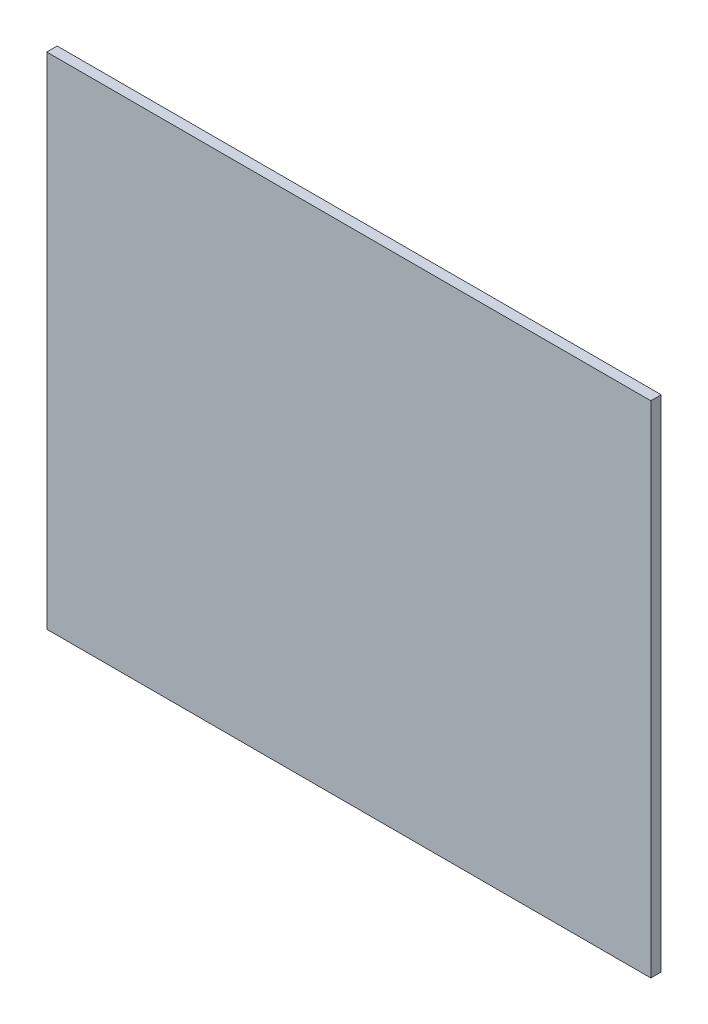
SolidWorks part; units mm, degrees
ref_plane "前视基准面" through (0, 0, 0) normal (0, 0, 1) x (1, 0, 0)
ref_plane "上视基准面" through (0, 0, 0) normal (0, 1, 0) x (1, 0, 0)
ref_plane "右视基准面" through (0, 0, 0) normal (1, 0, 0) x (0, 0, -1)
sketch "草图1" plane through (0, 0, 0) normal (0, 0, 1) x (1, 0, 0)
  line L1 (-29, 24) -> (0, 24)
  line L2 (-29, 24) -> (-29, 0)
  line L3 (-29, 0) -> (0, 0)
  line L4 (0, 24) -> (0, 0)
  dimension "D1" = 29
  dimension "D2" = 24
extrude "凸台-拉伸1" add sketch "草图1" along normal blind 0.5
